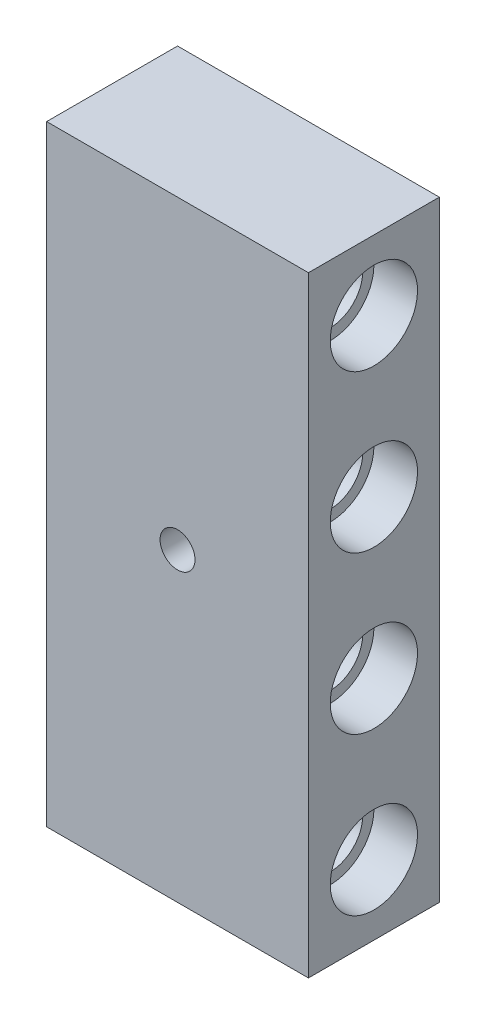
SolidWorks part; units mm, degrees
ref_plane "Front Plane" through (0, 0, 0) normal (0, 0, 1) x (1, 0, 0)
ref_plane "Top Plane" through (0, 0, 0) normal (0, 1, 0) x (1, 0, 0)
ref_plane "Right Plane" through (0, 0, 0) normal (1, 0, 0) x (0, 0, -1)
sketch "Sketch1" plane through (0, 0, 0) normal (0, 0, 1) x (1, 0, 0)
  line L1 (0, 0) -> (19.05, 0)
  line L2 (0, 0) -> (0, 44.45)
  line L3 (0, 44.45) -> (19.05, 44.45)
  line L4 (19.05, 0) -> (19.05, 44.45)
  circle A0 centre (9.525, 22.225) radius 1.27
  point P7 (9.525, 44.45)
  point P8 (19.05, 22.225)
  dimension "D4" = 2.54
  dimension "D1" = 19.05
  dimension "D2" = 44.45
extrude "Boss-Extrude1" add sketch "Sketch1" along normal blind 9.525
sketch "Sketch2" plane through (19.05, 0, 0) normal (1, 0, 0) x (0, 0, -1)
  line L0 (-9.525, 44.45) -> (0, 44.45) construction
  line L1 (-4.7625, 44.45) -> (-4.7625, 0) construction
  line L2 (-9.525, 0) -> (0, 0) construction
  line L4 (0, 0) -> (0, 44.45) construction
  line L5 (0, 22.225) -> (-9.525, 22.225) construction
  line L6 (-9.525, 0) -> (-9.525, 44.45) construction
  circle A0 centre (-4.7625, 16.51) radius 2.3622
  circle A1 centre (-4.7625, 39.37) radius 2.3622
  circle A2 centre (-4.7625, 27.94) radius 2.3622
  circle A3 centre (-4.7625, 5.08) radius 2.3622
  circle A5 centre (-4.7625, 27.94) radius 2.3622 [skipped]
  circle A6 centre (-4.7625, 39.37) radius 2.3622 [skipped]
  point P0 (0, 22.225)
  point P1 (0, 33.655)
  point P13 (0, 45.085)
  point P20 (0, 56.515)
  dimension "D1" = 4
  dimension "D5" = 4.7625
  dimension "D6" = 4.7244
  dimension "D2" = 11.43
  dimension "D3" = 5.08
  dimension "D4" = 11.43
extrude "Cut-Extrude1" cut sketch "Sketch2" against normal through all contours A2 | A1
sketch "Sketch4" plane through (19.05, 0, 0) normal (1, 0, 0) x (0, 0, -1)
  line L0 (-9.525, 0) -> (0, 0) construction
  line L1 (-9.525, 44.45) -> (-7.9375, 44.45)
  line L2 (-9.525, 44.45) -> (-9.525, 0)
  line L3 (-9.525, 0) -> (-7.9375, 0)
  line L4 (-7.9375, 44.45) -> (-7.9375, 0)
  line L6 (0, 44.45) -> (-1.5875, 44.45)
  line L7 (0, 44.45) -> (0, 0)
  line L8 (0, 0) -> (-1.5875, 0)
  line L9 (-1.5875, 44.45) -> (-1.5875, 0)
  dimension "D1" = 6.35
  dimension "D2" = 1.5875
ref_plane "Plane1" through (9.525, 0, 0) normal (1, 0, 0) x (0, 0, -1)
sketch "Sketch5" plane through (19.05, 0, 0) normal (1, 0, 0) x (0, 0, -1)
  line L0 (-9.525, 22.225) -> (0, 22.225) construction
  line L1 (-9.525, 0) -> (-9.525, 44.45) construction
  line L2 (0, 0) -> (0, 44.45) construction
  circle A0 centre (-4.7625, 39.37) radius 3.175
  circle A1 centre (-4.7625, 27.94) radius 3.175
  circle A29 centre (-4.7625, 5.08) radius 3.175
  circle A30 centre (-4.7625, 16.51) radius 3.175
  circle A33 centre (-4.7625, 27.94) radius 3.175 [skipped]
  circle A34 centre (-4.7625, 39.37) radius 3.175 [skipped]
  circle M1 centre (-4.7625, 5.08) radius 2.3622
  circle M2 centre (-4.7625, 16.51) radius 2.3622
  circle M13 centre (-4.7625, 39.37) radius 2.3622
  circle M14 centre (-4.7625, 27.94) radius 2.3622
  dimension "D1" = 6.35
  dimension "D4" = 11.43
  dimension "D2" = 4
extrude "Cut-Extrude2" cut sketch "Sketch5" against normal blind 3.175 contours A29 M1 | A30 M2 | A1 M14 | A0 M13
mirror "Mirror1" about plane through (9.525, 0, 0) normal (1, 0, 0) of "Cut-Extrude2"
